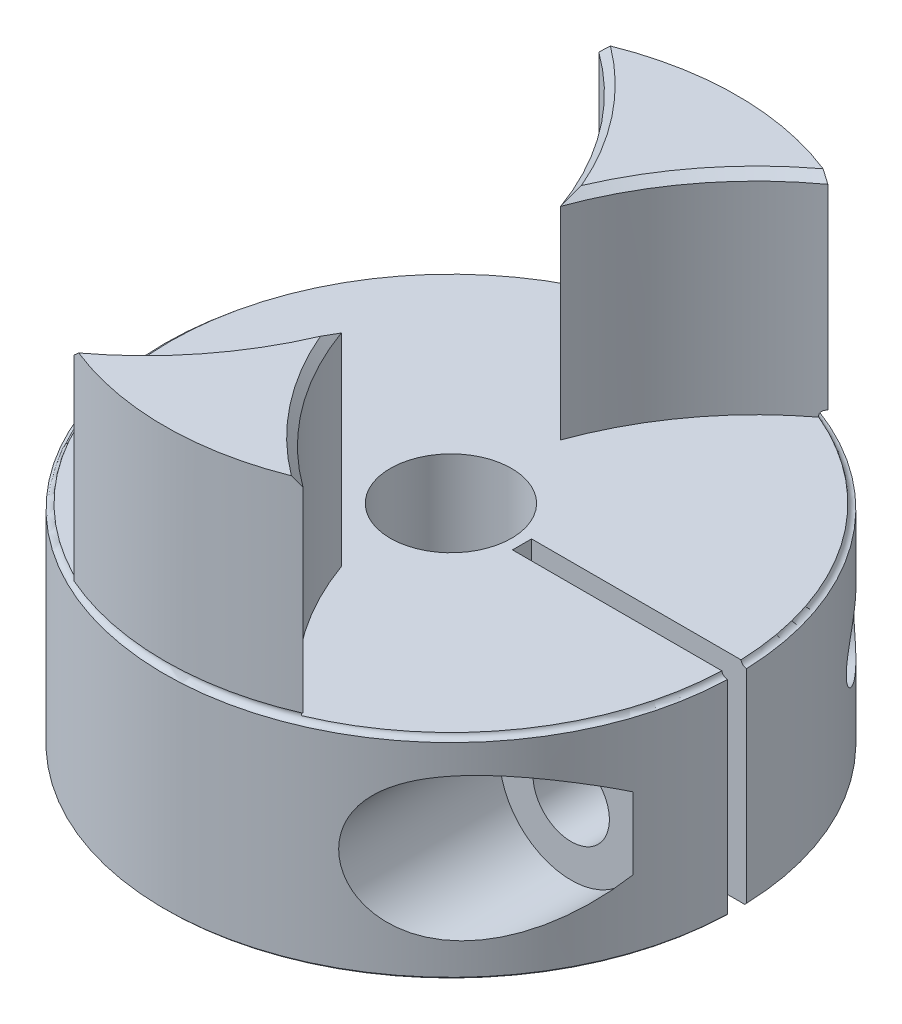
SolidWorks part; units mm, degrees
material "1060 Alloy"
ref_plane "Front" through (0, 0, 0) normal (0, 0, 1) x (1, 0, 0)
ref_plane "Top" through (0, 0, 0) normal (0, 1, 0) x (1, 0, 0)
ref_plane "Right" through (0, 0, 0) normal (1, 0, 0) x (0, 0, -1)
sketch "Sketch1" plane through (0, 0, 0) normal (0, 1, 0) x (1, 0, 0)
  circle A0 centre (0, 0) radius 15
extrude "Boss-Extrude1" add sketch "Sketch1" along normal mid plane 22
sketch "Sketch2" plane through (0, 11, 0) normal (0, 1, 0) x (1, 0, 0)
  circle A0 centre (0, 0) radius 3.175
  dimension "D1" = 6.35
extrude "Cut-Extrude1" cut sketch "Sketch2" against normal blind 23
sketch "Sketch3" plane through (0, 11, 0) normal (0, 1, 0) x (1, 0, 0)
  line L0 (-19.0209, 0) -> (26.8019, 0) construction
  line L1 (0, 17.1133) -> (0, -22.8638) construction
  line L2 (6, 13.7477) -> (6, 19.4636) construction
  circle A0 centre (16, 0) radius 17
  circle A1 centre (0, 0) radius 15 construction
  circle A2 centre (0, 0) radius 15 construction
  dimension "D2" = 34
  dimension "D1" = 6
extrude "Cut-Extrude2" cut sketch "Sketch3" against normal blind 11
sketch "Sketch4" plane through (0, 11, 0) normal (0, 1, 0) x (1, 0, 0)
  line L0 (0, 15) -> (0, -15) construction
  line L1 (-15, 0) -> (15, 0) construction
  arc A0 (6, 13.7477) -> (6, -13.7477) centre (0, 0) ccw construction
  arc A1 (6, -13.7477) -> (6, 13.7477) centre (0, 0) ccw construction
  arc A4 (-0.7162, -3.0932) -> (6, -13.7477) centre (16, 0) ccw construction
  arc A6 (-0.7162, 3.0932) -> (-0.7162, -3.0932) centre (0, 0) ccw construction
  arc A8 (-6, 13.7477) -> (-6, -13.7477) centre (0, 0) ccw
  arc A9 (0.7162, -3.0932) -> (-6, -13.7477) centre (-16, 0) cw
  arc A10 (-6, 13.7477) -> (0.7162, 3.0932) centre (-16, 0) cw
  arc A11 (0.7162, 3.0932) -> (0.7162, -3.0932) centre (0, 0) ccw
extrude "Cut-Extrude3" cut sketch "Sketch4" against normal blind 11
sketch "Sketch5" plane through (0, 0, 0) normal (0, 1, 0) x (1, 0, 0)
  line L0 (0, 0) -> (23.6149, 0) construction
  line L2 (3.7246, 0.5) -> (19.8903, 0.5)
  line L3 (3.7246, 0.5) -> (3.7246, -0.5)
  line L4 (3.7246, -0.5) -> (19.8903, -0.5)
  line L5 (19.8903, 0.5) -> (19.8903, -0.5)
  line L6 (3.7246, 0.5) -> (19.8903, -0.5) construction
  line L7 (3.7246, -0.5) -> (19.8903, 0.5) construction
  point P3 (11.8074, 0)
  dimension "D1" = 1
extrude "Cut-Extrude4" cut sketch "Sketch5" against normal blind 21
sketch "Sketch6" plane through (0, 0, 0) normal (0, 0, 1) x (1, 0, 0)
  line L0 (0, 17.6778) -> (0, -16.8659) construction
  line L1 (-15, -5.5) -> (14.9917, -5.5) construction
  line L2 (-15, 0) -> (-15, -11) construction
  line L3 (14.9917, -11) -> (14.9917, 0) construction
  circle A0 centre (11, -5.5) radius 2
  dimension "D1" = 11
  dimension "D2" = 4
extrude "Cut-Extrude5" cut sketch "Sketch6" along normal blind 21
sketch "Sketch7" plane through (0, 0, 0.5) normal (0, 0, -1) x (-1, 0, 0)
  circle A0 centre (-11, -5.5) radius 3.75
extrude "Cut-Extrude6" cut sketch "Sketch7" against normal blind 21 from offset 4.2 offset against normal yes
hole_wizard "M4 Tapped Hole1" positions "Sketch8" profile "Sketch9" tap size "M4" standard "ISO"
sketch "Sketch8" plane through (0, 0, -0.5) normal (0, 0, 1) x (1, 0, 0)
  point P0 (11, -5.5)
sketch "Sketch9" plane through (11, -5.5, -0.5) normal (1, 0, 0) x (0, -1, 0)
  line L0 (0, 0) -> (0, 21.0914)
  line L1 (0, 21.0914) -> (1.65, 20.1)
  line L2 (1.65, 20.1) -> (1.65, 0)
  line L5 (1.65, 0) -> (0, 0)
  line L10 (0, 21.0914) -> (-1.65, 20.1) construction
  line L11 (0, -6.35) -> (0, 107.95) construction
  dimension "Tap Drill Dia." = 3.3
  dimension "Tap Drill Depth" = 20.1
  dimension "Drill Angle" = 118
cosmetic thread "Hole Thread1" parameters "D1"=11.2293, "D2"=4
chamfer "Chamfer2" distance 0.1 angle 45 1 edges at (-15, -11, 0)
chamfer "Pah1" distance 0.4 angle 45 4 edges at (-2.3981, 11, 10.1974) (2.3981, 11, 10.1974) (-2.3981, 11, -10.1974) (2.3981, 11, -10.1974)
sketch "Çizim1" plane through (0, 0, 0) normal (1, 0, 0) x (0, 0, -1)
  line L0 (0, -10.9) -> (0, 0) construction
  line L1 (15, -10.9) -> (-15, -10.9) construction
  line L2 (0, 0) -> (15, 0.05) construction
  line L3 (15, -10.9) -> (15, 11) construction
  circle A0 centre (15, 0.05) radius 0.3
  dimension "D1" = 0.6
revolve "Kes-Döndür4" cut sketch "Çizim1" angle 360 about L0
